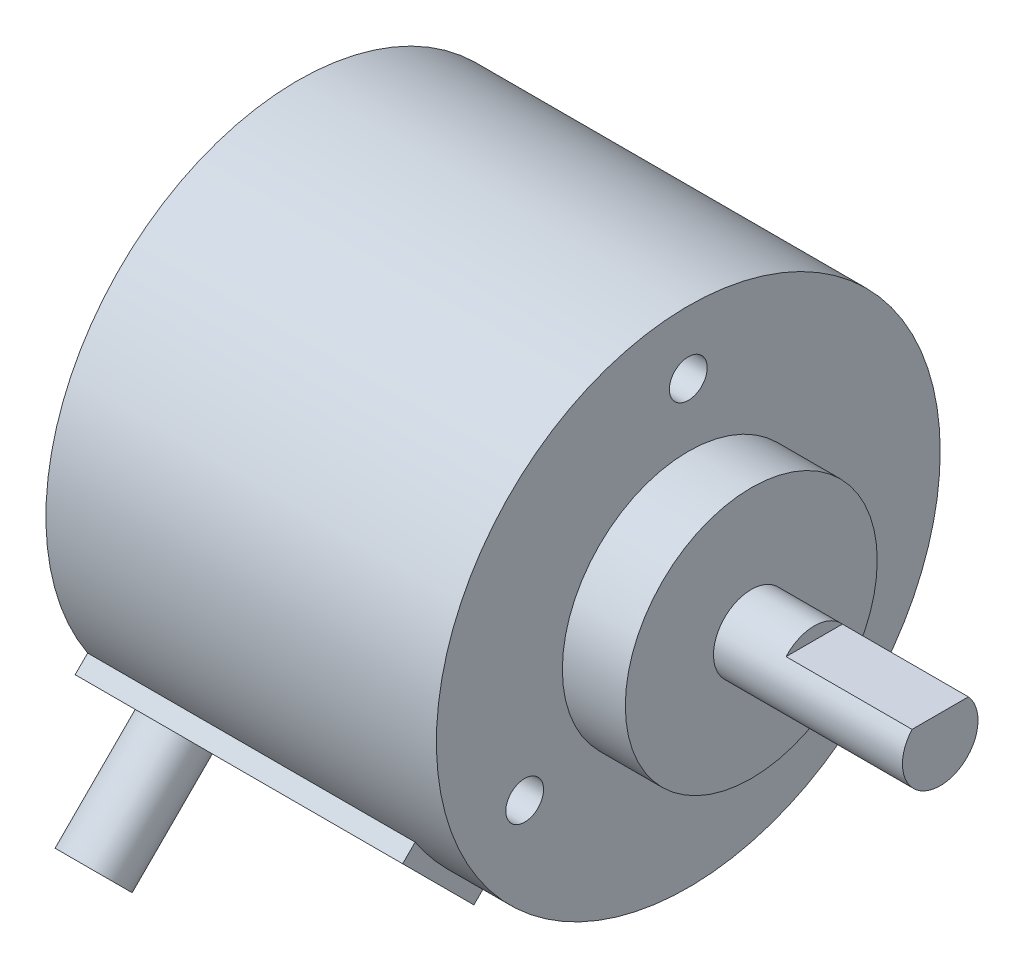
SolidWorks part; units mm, degrees
ref_plane "Спереди" through (0, 0, 0) normal (0, 0, 1) x (1, 0, 0)
ref_plane "Сверху" through (0, 0, 0) normal (0, 1, 0) x (1, 0, 0)
ref_plane "Справа" through (0, 0, 0) normal (1, 0, 0) x (0, 0, -1)
sketch "Эскиз1" plane through (0, 0, 0) normal (1, 0, 0) x (0, 0, -1)
  circle A0 centre (0, 0) radius 20
  dimension "D1" = 40
extrude "Бобышка-Вытянуть1" add sketch "Эскиз1" along normal blind 5
sketch "Эскиз2" plane through (5, 0, 0) normal (1, 0, 0) x (0, 0, -1)
  circle A0 centre (0, 0) radius 10
  dimension "D1" = 20
extrude "Бобышка-Вытянуть2" add sketch "Эскиз2" along normal blind 5
sketch "Эскиз3" plane through (5, 0, 0) normal (1, 0, 0) x (0, 0, -1)
  line L0 (0, 0) -> (0, 15) construction
  circle A0 centre (0, 15) radius 1.5
  circle A1 centre (12.9904, -7.5) radius 1.5
  circle A2 centre (-12.9904, -7.5) radius 1.5
  circle A3 centre (0, 0) radius 15 construction
  point P9 (0, 0)
  dimension "D1" = 3
  dimension "D3" = 30
  dimension "D4" = 25.9808
  dimension "D2" = 3
extrude "Вырез-Вытянуть1" cut sketch "Эскиз3" against normal blind 5
sketch "Эскиз4" plane through (10, 0, 0) normal (1, 0, 0) x (0, 0, -1)
  circle A0 centre (0, 0) radius 3
  dimension "D1" = 6
extrude "Бобышка-Вытянуть3" add sketch "Эскиз4" along normal blind 5
sketch "Эскиз5" plane through (15, 0, 0) normal (1, 0, 0) x (0, 0, -1)
  line L0 (-2.2361, 2) -> (2.2361, 2)
  line L1 (0, 0) -> (0, 2) construction
  line L2 (0, 0) -> (0, -3) construction
  circle A0 centre (0, 0) radius 3 construction
  arc A1 (-2.2361, 2) -> (2.2361, 2) centre (0, 0) ccw
  dimension "D1" = 5
extrude "Бобышка-Вытянуть4" add sketch "Эскиз5" along normal blind 10
sketch "Эскиз6" plane through (0, 0, 0) normal (-1, 0, 0) x (0, 0, 1)
  circle A0 centre (0, 0) radius 20
  circle A1 centre (0, 0) radius 20 construction
extrude "Бобышка-Вытянуть5" add sketch "Эскиз6" along normal blind 26
sketch "Эскиз7" plane through (-26, 0, 0) normal (-1, 0, 0) x (0, 0, 1)
  line L0 (0, 0) -> (0, 20) construction
  line L1 (0, 0) -> (14.1421, -14.1421) construction
  circle A0 centre (0, 0) radius 20 construction
  dimension "D1" = 135
ref_plane "Плоскость1" through (0, -14.1421, 14.1421) normal (0, -0.7071, 0.7071) x (-1, 0, 0)
sketch "Эскиз8" plane through (0, -14.1421, 14.1421) normal (0, -0.7071, 0.7071) x (-1, 0, 0)
  line L0 (26, -20) -> (26, 20) construction
  line L1 (0, 0) -> (21, 0) construction
  circle A0 centre (21, 0) radius 2.5
  dimension "D1" = 5
  dimension "D2" = 5
extrude "Бобышка-Вытянуть6" add sketch "Эскиз8" along normal blind 10 and the other way up to surface other way up to face at (5, 0, -20)
sketch "Эскиз9" plane through (0, -14.1421, 14.1421) normal (0, -0.7071, 0.7071) x (-1, 0, 0)
  line L0 (13, 0) -> (0, 0) construction
  line L1 (26, -4) -> (0, -4)
  line L2 (26, -4) -> (26, 4)
  line L3 (26, 4) -> (0, 4)
  line L4 (0, -4) -> (0, 4)
  line L5 (26, -4) -> (0, 4) construction
  line L6 (26, 4) -> (0, -4) construction
  line L7 (26, -20) -> (26, 20) construction
  line L8 (-5, 20) -> (-5, -20) construction
  point P0 (13, 0)
  dimension "D1" = 8
  dimension "D2" = 5
extrude "Бобышка-Вытянуть7" add sketch "Эскиз9" along normal blind 1 and the other way up to surface other way up to face at (-26, 0, 20)
